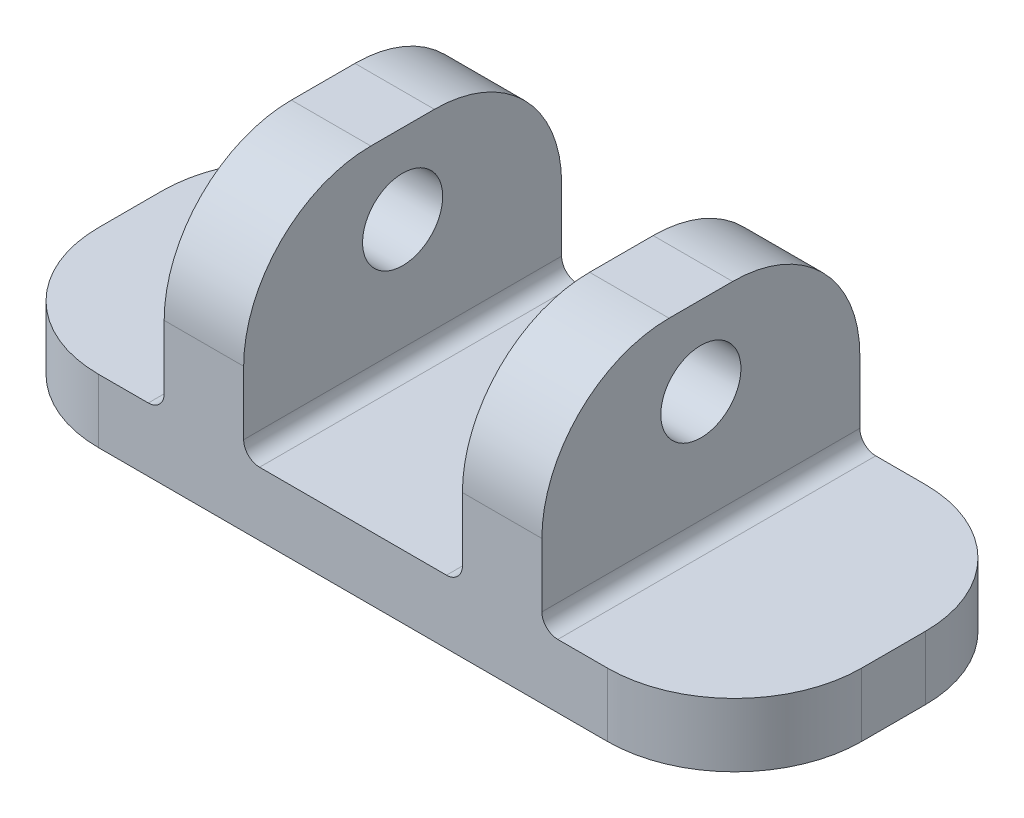
SolidWorks part; units mm, degrees
material "Plain Carbon Steel"
ref_plane "Front Plane" through (0, 0, 0) normal (0, 0, 1) x (1, 0, 0)
ref_plane "Top Plane" through (0, 0, 0) normal (0, 1, 0) x (1, 0, 0)
ref_plane "Right Plane" through (0, 0, 0) normal (1, 0, 0) x (0, 0, -1)
sketch "Sketch1" plane through (0, 0, 0) normal (0, 0, 1) x (1, 0, 0)
  line L0 (0, 0) -> (0, 61.1288) construction
  line L1 (0, 0) -> (48.3891, 0) construction
  line L2 (10.922, 7.9375) -> (18.8595, 7.9375)
  line L3 (18.8595, 7.9375) -> (18.8595, -12.7)
  line L4 (38.1, -19.05) -> (-38.1, -19.05)
  line L5 (10.922, 7.9375) -> (10.922, -12.7)
  line L6 (10.922, -12.7) -> (-10.922, -12.7)
  line L7 (-10.922, 7.9375) -> (-10.922, -12.7)
  line L8 (-38.1, -12.7) -> (-38.1, -19.05)
  line L9 (-10.922, 7.9375) -> (-18.8595, 7.9375)
  line L10 (18.8595, -12.7) -> (38.1, -12.7)
  line L11 (38.1, -12.7) -> (38.1, -19.05)
  line L12 (-18.8595, 7.9375) -> (-18.8595, -12.7)
  line L13 (-18.8595, -12.7) -> (-38.1, -12.7)
  point P11 (0, -12.7)
  point P13 (0, -19.05)
  dimension "D1" = 6.35
  dimension "D2" = 7.9375
  dimension "D3" = 12.7
  dimension "D4" = 21.844
  dimension "D5" = 7.9375
  dimension "D6" = 76.2
extrude "Boss-Extrude1" add sketch "Sketch1" along normal mid plane 31.75
sketch "Sketch2" plane through (0, 0, 0) normal (1, 0, 0) x (0, 0, -1)
  circle A0 centre (0, 0) radius 4
  dimension "D1" = 8
extrude "Cut-Extrude1" cut sketch "Sketch2" against normal through all and the other way through all
fillet "Fillet1" radius 12.7 4 edges at (-14.8908, 7.9375, -15.875) (-14.8908, 7.9375, 15.875) (14.8908, 7.9375, -15.875) (14.8908, 7.9375, 15.875)
fillet "Fillet2" radius 1.5875 4 edges at (10.922, -12.7, 0) (-10.922, -12.7, 0) (-18.8595, -12.7, 0) (18.8595, -12.7, 0)
sketch "Sketch3" plane through (0, -19.05, 0) normal (0, -1, 0) x (1, 0, 0)
  line L0 (0, 0) -> (0, 14.7427) construction
  point P3 (-19.05, 0)
  point P4 (19.05, 0)
  dimension "D1" = 38.1
fillet "Fillet3" radius 12.7 4 edges at (-38.1, -15.875, -15.875) (38.1, -15.875, -15.875) (38.1, -15.875, 15.875) (-38.1, -15.875, 15.875)
